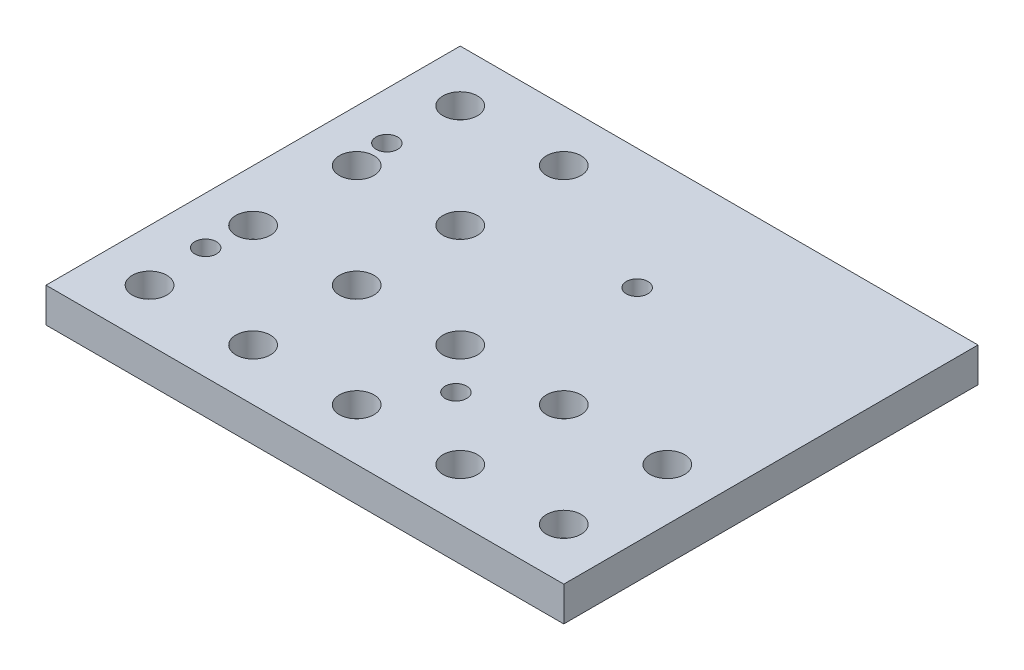
SolidWorks part; units mm, degrees
material "6061-T6 (SS)"
ref_plane "Front" through (0, 0, 0) normal (0, 0, 1) x (1, 0, 0)
ref_plane "Top" through (0, 0, 0) normal (0, 1, 0) x (1, 0, 0)
ref_plane "Right" through (0, 0, 0) normal (1, 0, 0) x (0, 0, -1)
sketch "Sketch1" plane through (0, 0, 0) normal (0, 1, 0) x (1, 0, 0)
  line L1 (0, 0) -> (190.5, 0)
  line L2 (0, 0) -> (0, 152.4)
  line L3 (0, 152.4) -> (190.5, 152.4)
  line L4 (190.5, 0) -> (190.5, 152.4)
  dimension "D1" = 190.5
  dimension "D2" = 152.4
extrude "Boss-Extrude1" add sketch "Sketch1" along normal blind 12.7
hole_wizard "CBORE for 1/4 Binding Head Machine Screw1" positions "Sketch2" profile "Sketch3" counterbore size "1/4" standard "ANSI Inch"
sketch "Sketch2" plane through (0, 12.7, 0) normal (0, 1, 0) x (1, 0, 0)
  line L0 (0, 0) -> (190.5, 0) construction
  line L1 (0, 152.4) -> (0, 0) construction
  point P0 (19.05, 19.05)
  point P2 (57.15, 19.05)
  point P4 (95.25, 19.05)
  point P6 (133.35, 19.05)
  point P8 (19.05, 57.15)
  point P10 (19.05, 95.25)
  point P12 (19.05, 133.35)
  point P14 (57.15, 57.15)
  point P16 (95.25, 57.15)
  point P18 (133.35, 57.15)
  point P20 (57.15, 95.25)
  point P22 (57.15, 133.35)
  dimension "D1" = 19.05
  dimension "D2" = 19.05
  dimension "D3" = 19.05
  dimension "D4" = 19.05
  dimension "D5" = 19.05
  dimension "D6" = 19.05
  dimension "D7" = 19.05
  dimension "D8" = 19.05
  dimension "D9" = 57.15
  dimension "D10" = 57.15
  dimension "D11" = 57.15
  dimension "D12" = 57.15
  dimension "D13" = 57.15
  dimension "D14" = 57.15
  dimension "D15" = 57.15
  dimension "D16" = 57.15
  dimension "D17" = 95.25
  dimension "D18" = 95.25
  dimension "D19" = 95.25
  dimension "D20" = 95.25
  dimension "D21" = 133.35
  dimension "D22" = 133.35
  dimension "D23" = 133.35
  dimension "D24" = 133.35
sketch "Sketch3" plane through (19.05, 12.7, -19.05) normal (1, 0, 0) x (0, 0, 1)
  line L0 (0, 0) -> (0, 12.7)
  line L1 (0, 12.7) -> (4.1656, 12.7)
  line L3 (4.1656, 12.7) -> (4.1656, 8.89)
  line L4 (4.1656, 8.89) -> (6.35, 8.89)
  line L5 (6.35, 8.89) -> (6.35, 0)
  line L7 (6.35, 0) -> (0, 0)
  line L11 (0, -6.35) -> (0, 107.95) construction
  dimension "Thru Hole Dia." = 8.3312
  dimension "Thru Hole Depth" = 12.7
  dimension "C'Bore Dia." = 12.7
  dimension "C'Bore Depth" = 8.89
hole_wizard "CBORE for 1/4 Binding Head Machine Screw2" positions "Sketch4" profile "Sketch5" counterbore size "1/4" standard "ANSI Inch"
sketch "Sketch4" plane through (0, 12.7, 0) normal (0, 1, 0) x (1, 0, 0)
  line L0 (0, 0) -> (190.5, 0) construction
  line L1 (0, 152.4) -> (0, 0) construction
  point P0 (171.45, 19.05)
  point P2 (171.45, 57.15)
  dimension "D1" = 19.05
  dimension "D2" = 57.15
  dimension "D3" = 171.45
  dimension "D4" = 171.45
sketch "Sketch5" plane through (171.45, 12.7, -19.05) normal (1, 0, 0) x (0, 0, 1)
  line L0 (0, 0) -> (0, 12.7)
  line L1 (0, 12.7) -> (4.1656, 12.7)
  line L3 (4.1656, 12.7) -> (4.1656, 8.89)
  line L4 (4.1656, 8.89) -> (6.35, 8.89)
  line L5 (6.35, 8.89) -> (6.35, 0)
  line L7 (6.35, 0) -> (0, 0)
  line L11 (0, -6.35) -> (0, 107.95) construction
  dimension "Thru Hole Dia." = 8.3312
  dimension "Thru Hole Depth" = 12.7
  dimension "C'Bore Dia." = 12.7
  dimension "C'Bore Depth" = 8.89
hole_wizard "3/8-16 Tapped Hole1" positions "Sketch6" profile "Sketch7" tap size "3/8-16" standard "ANSI Inch"
sketch "Sketch6" plane through (0, 12.7, 0) normal (0, 1, 0) x (1, 0, 0)
  line L0 (0, 0) -> (190.5, 0) construction
  line L1 (0, 152.4) -> (0, 0) construction
  point P0 (17.4625, 41.275)
  dimension "D1" = 41.275
  dimension "D2" = 17.4625
sketch "Sketch7" plane through (17.4625, 12.7, -41.275) normal (1, 0, 0) x (0, 0, 1)
  line L0 (0, 0) -> (0, 12.7)
  line L1 (0, 12.7) -> (3.9687, 12.7)
  line L2 (3.9687, 12.7) -> (3.9687, 0)
  line L5 (3.9687, 0) -> (0, 0)
  line L11 (0, -6.35) -> (0, 107.95) construction
  dimension "Thru Tap Drill Dia." = 7.9375
  dimension "Thru Tap Drill Depth" = 12.7
cosmetic thread "Hole Thread1" parameters "D2"=9.525
pattern_linear "LPattern1" count 2 spacing 92.075 along (1, 0, 0) count 2 spacing 66.675 along (0, 0, -1) of "3/8-16 Tapped Hole1"
